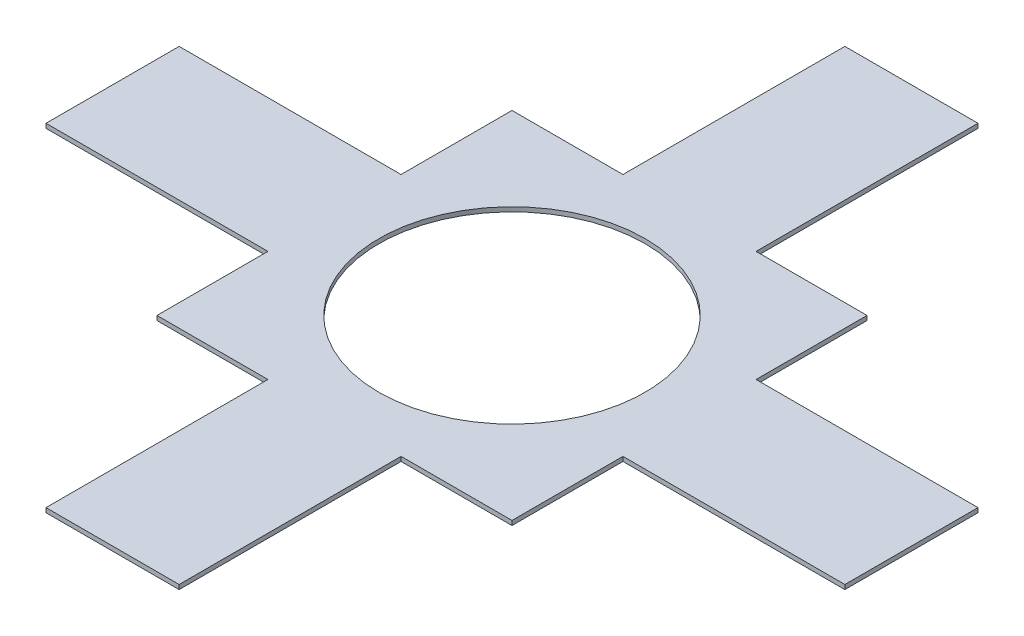
SolidWorks part; units mm, degrees
ref_plane "Front Plane" through (0, 0, 0) normal (0, 0, 1) x (1, 0, 0)
ref_plane "Top Plane" through (0, 0, 0) normal (0, 1, 0) x (1, 0, 0)
ref_plane "Right Plane" through (0, 0, 0) normal (1, 0, 0) x (0, 0, -1)
sketch "Sketch1" plane through (0, 0, 0) normal (0, 1, 0) x (1, 0, 0)
  line L0 (-1.5, 4) -> (-1.5, 9)
  line L1 (-4, 4) -> (-1.5, 4)
  line L2 (-4, 4) -> (-4, 1.5)
  line L3 (-4, -4) -> (-1.5, -4)
  line L4 (4, 4) -> (4, 1.5)
  line L5 (-1.5, 9) -> (1.5, 9)
  line L6 (1.5, 9) -> (1.5, 4)
  line L7 (-4, -1.5) -> (-9, -1.5)
  line L8 (-9, -1.5) -> (-9, 1.5)
  line L9 (-9, 1.5) -> (-4, 1.5)
  line L10 (1.5, -4) -> (1.5, -9)
  line L11 (1.5, -9) -> (-1.5, -9)
  line L12 (-1.5, -9) -> (-1.5, -4)
  line L13 (4, 1.5) -> (9, 1.5)
  line L14 (9, 1.5) -> (9, -1.5)
  line L15 (9, -1.5) -> (4, -1.5)
  line L16 (1.5, 4) -> (4, 4)
  line L17 (-4, -1.5) -> (-4, -4)
  line L18 (1.5, -4) -> (4, -4)
  line L19 (4, -1.5) -> (4, -4)
  circle A0 centre (0, 0) radius 3
  point P24 (0, 0)
  dimension "D16" = 6
  dimension "D1" = 4
  dimension "D2" = 4
  dimension "D3" = 4
  dimension "D4" = 4
  dimension "D5" = 3
  dimension "D6" = 2.5
  dimension "D7" = 5
  dimension "D9" = 2.5
  dimension "D10" = 2.5
  dimension "D8" = 2.5
  dimension "D11" = 2.5
  dimension "D12" = 3
  dimension "D13" = 3
  dimension "D14" = 2.5
  dimension "D15" = 2.5
  dimension "D17" = 5
  dimension "D18" = 5
  dimension "D19" = 5
  dimension "D20" = 90
extrude "Boss-Extrude1" add sketch "Sketch1" along normal blind 0.1
